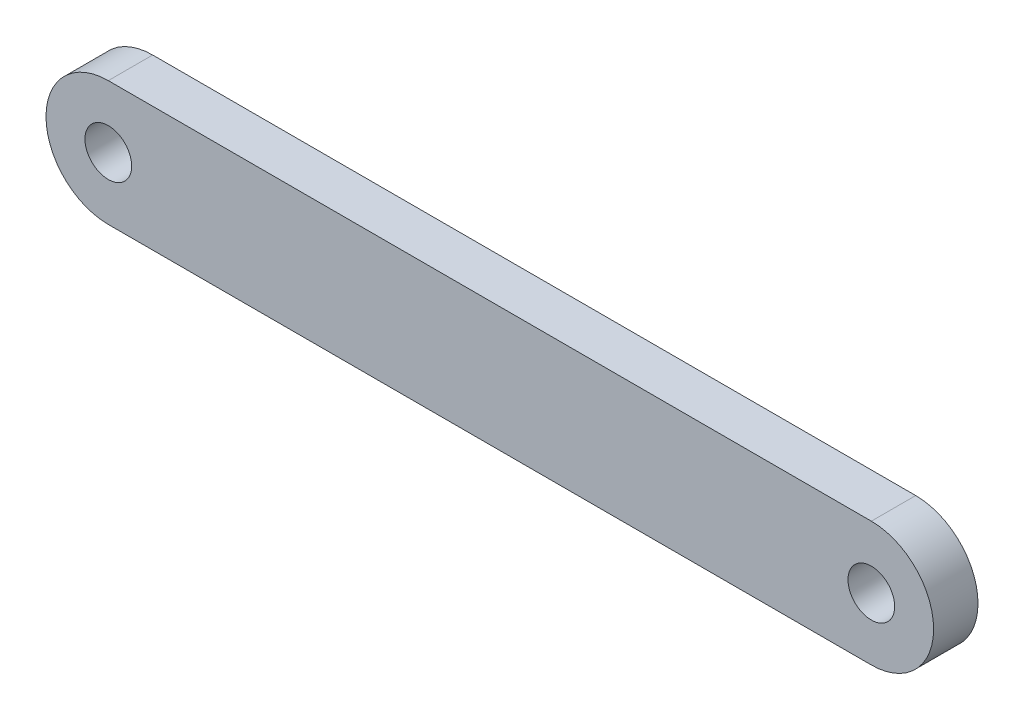
SolidWorks part; units mm, degrees
material "Pine"
ref_plane "Front" through (0, 0, 0) normal (0, 0, 1) x (1, 0, 0)
ref_plane "Top" through (0, 0, 0) normal (0, 1, 0) x (1, 0, 0)
ref_plane "Right" through (0, 0, 0) normal (1, 0, 0) x (0, 0, -1)
sketch "Sketch1" plane through (0, 0, 0) normal (0, 0, 1) x (1, 0, 0)
  line L1 (-28.5, 4) -> (28.5, 4)
  line L2 (-28.5, 4) -> (-28.5, -4)
  line L3 (-28.5, -4) -> (28.5, -4)
  line L4 (28.5, 4) -> (28.5, -4)
  line L5 (-28.5, 4) -> (28.5, -4) construction
  line L6 (-28.5, -4) -> (28.5, 4) construction
  point P0 (0, 0)
  dimension "D1" = 57
  dimension "D2" = 8
extrude "Boss-Extrude1" add sketch "Sketch1" along normal blind 2.85
sketch "Sketch2" plane through (0, 0, 2.85) normal (0, 0, 1) x (1, 0, 0)
  line L0 (24.5, -4) -> (29.5, -4)
  line L1 (29.5, -4) -> (29.5, 4)
  line L2 (29.5, 4) -> (24.5, 4)
  line L3 (28.5, -4) -> (28.5, 4) construction
  line L4 (28.5, 4) -> (-28.5, 4) construction
  line L5 (-28.5, -4) -> (28.5, -4) construction
  arc A0 (24.5, -4) -> (24.5, 4) centre (24.5, 0) ccw
  dimension "D1" = 1
extrude "Cut-Extrude1" cut sketch "Sketch2" against normal through all
sketch "Sketch3" plane through (0, 0, 2.85) normal (0, 0, 1) x (1, 0, 0)
  circle A0 centre (24.5, 0) radius 1.5
  dimension "D1" = 3
extrude "Cut-Extrude2" cut sketch "Sketch3" against normal through all
mirror "Mirror1" about plane through (0, 0, 0) normal (1, 0, 0) of "Cut-Extrude2", "Cut-Extrude1"
